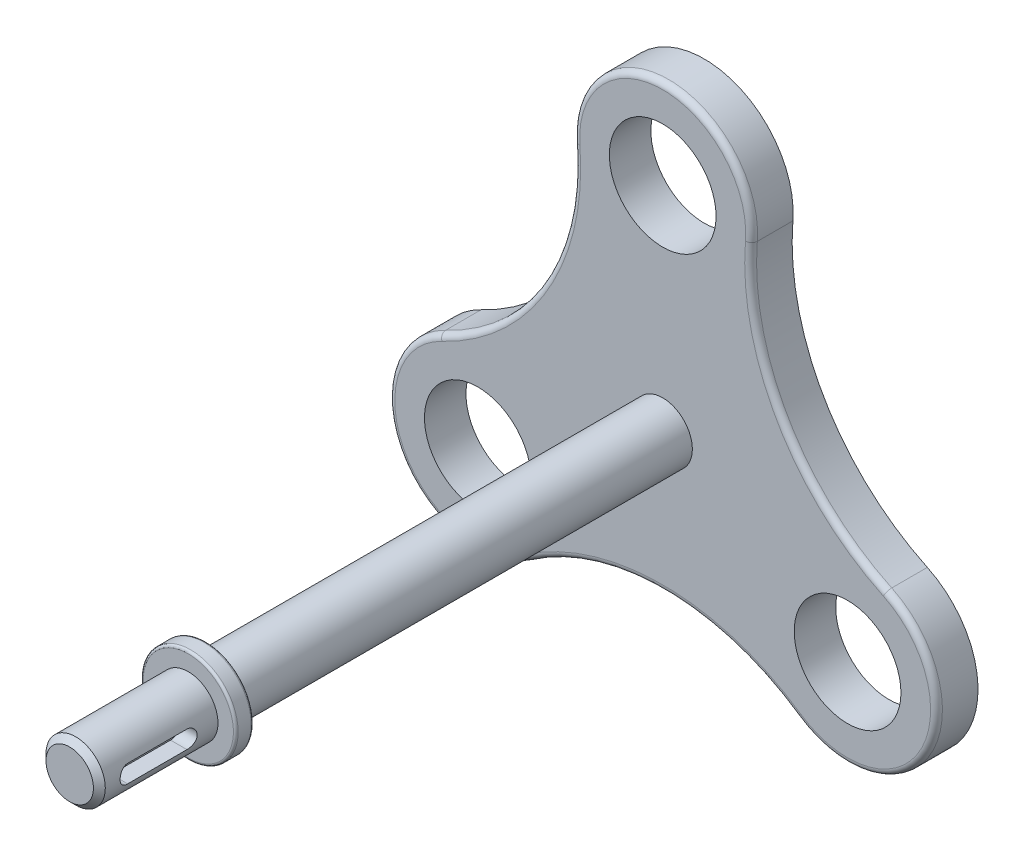
SolidWorks part; units mm, degrees
ref_plane "Front Plane" through (0, 0, 0) normal (0, 0, 1) x (1, 0, 0)
ref_plane "Top Plane" through (0, 0, 0) normal (0, 1, 0) x (1, 0, 0)
ref_plane "Right Plane" through (0, 0, 0) normal (1, 0, 0) x (0, 0, -1)
sketch "Sketch1" plane through (0, 0, 0) normal (0, 0, 1) x (1, 0, 0)
  line L0 (0, 27.5674) -> (0, -22.1615) construction
  line L1 (0, 0) -> (15.5885, -9) construction
  line L2 (0, 0) -> (-15.5885, -9) construction
  circle A6 centre (0, 18) radius 4.5
  arc A7 (7.4766, 17.4075) -> (-7.4766, 17.4075) centre (0, 18) ccw
  arc A8 (11.3371, -15.1786) -> (18.8136, -2.2289) centre (15.5885, -9) ccw
  circle A9 centre (15.5885, -9) radius 4.5
  arc A10 (-18.8136, -2.2289) -> (-11.3371, -15.1786) centre (-15.5885, -9) ccw
  circle A11 centre (-15.5885, -9) radius 4.5
  arc A12 (-18.8136, -2.2289) -> (-7.4766, 17.4075) centre (-27.4141, 15.8275) ccw
  arc A13 (18.8136, -2.2289) -> (7.4766, 17.4075) centre (27.4141, 15.8275) cw
  arc A14 (-11.3371, -15.1786) -> (11.3371, -15.1786) centre (0, -31.655) cw
  point P17 (0, 0)
  dimension "D2" = 9
  dimension "D3" = 7.5
  dimension "D5" = 20
  dimension "D6" = 20
  dimension "D8" = 7.5
  dimension "D1" = 18
  dimension "D7" = 120
  dimension "D4" = 3
extrude "Boss-Extrude1" add sketch "Sketch1" along normal blind 3.5
sketch "Sketch2" plane through (0, 0, 0) normal (1, 0, 0) x (0, 0, -1)
  line L0 (-49.5969, 0) -> (0, 0) construction
  line L1 (-53.5, 2.5) -> (-43.5, 2.5)
  line L2 (-43.5, 2.5) -> (-43.5, 4)
  line L3 (-43.5, 4) -> (-42, 4)
  line L4 (-42, 4) -> (-42, 2.5)
  line L5 (-42, 2.5) -> (-3.5, 2.5)
  line L6 (-3.5, 17.4075) -> (-3.5, -2.2289) construction
  line L7 (-53.5, 2.5) -> (-53.5, 0)
  line L8 (-3.5, 2.5) -> (-3.5, 0)
  line L9 (-53.5, 0) -> (-3.5, 0)
  dimension "D1" = 2.5
  dimension "D2" = 4
  dimension "D3" = 2.5
  dimension "D4" = 1.5
  dimension "D5" = 50
  dimension "D6" = 10
revolve "Revolve4" add sketch "Sketch2" angle 360 about L0
ref_plane "Plane2" through (2.5, 0, 0) normal (1, 0, 0) x (0, 0, -1)
sketch "Sketch6" plane through (2.5, 0, 0) normal (1, 0, 0) x (0, 0, -1)
  line L0 (-51, 0) -> (-46, 0) construction
  line L1 (-51, 0.75) -> (-46, 0.75)
  line L2 (-51, -0.75) -> (-46, -0.75)
  line L3 (-53.5, 2.5) -> (-53.5, -2.5) construction
  arc A0 (-51, 0.75) -> (-51, -0.75) centre (-51, 0) ccw
  arc A1 (-46, -0.75) -> (-46, 0.75) centre (-46, 0) ccw
  point P2 (-48.5, 0)
  dimension "D3" = 0.75
  dimension "D1" = 5
  dimension "D2" = 5
extrude "Cut-Extrude1" cut sketch "Sketch6" against normal blind 1.5
fillet "Fillet1" radius 0.5 6 edges at (22.0836, -12.75, 3.5) (0, -11.655, 3.5) (-22.0836, -12.75, 3.5) (-10.0935, 5.8275, 3.5) (0, 25.5, 3.5) (10.0935, 5.8275, 3.5)
fillet "Fillet2" radius 0.2 2 edges at (4, 0, 43.5) (4, 0, 42)
chamfer "Chamfer1" distance 0.5 angle 45 1 edges at (2.5, 0, 53.5)
